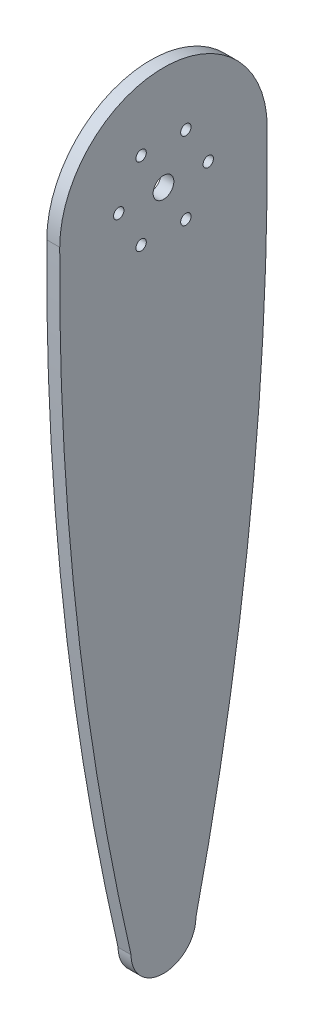
SolidWorks part; units mm, degrees
ref_plane "前视基准面" through (0, 0, 0) normal (0, 0, 1) x (1, 0, 0)
ref_plane "上视基准面" through (0, 0, 0) normal (0, 1, 0) x (1, 0, 0)
ref_plane "右视基准面" through (0, 0, 0) normal (1, 0, 0) x (0, 0, -1)
other "Configuration Table"
sketch "草图1" plane through (0, 0, 0) normal (1, 0, 0) x (0, 0, -1)
  line L0 (0, 12.5) -> (0, 250) construction
  arc A0 (-12.5, 0) -> (12.5, 0) centre (0, 0) ccw
  arc A1 (40, 250) -> (-40, 250) centre (0, 250) ccw
  arc A2 (-40, 250) -> (-12.5, 0) centre (1036.9037, 241.9469) ccw
  arc A3 (40, 250) -> (12.5, 0) centre (-1036.9037, 241.9469) cw
  dimension "D1" = 25
  dimension "D2" = 80
  dimension "D3" = 250
extrude "凸台-拉伸1" add sketch "草图1" along normal blind 5
sketch "草图2" plane through (0, 0, 0) normal (-1, 0, 0) x (0, 0, 1)
  circle A1 centre (17.25, 250) radius 2
  circle A2 centre (8.625, 235.0611) radius 2
  circle A3 centre (-8.625, 235.0611) radius 2
  circle A4 centre (-17.25, 250) radius 2
  circle A5 centre (-8.625, 264.9389) radius 2
  circle A6 centre (8.625, 264.9389) radius 2
  circle A7 centre (0, 250) radius 4
  point P17 (0, 250)
  dimension "D2" = 6
extrude "切除-拉伸1" cut sketch "草图2" against normal through all
